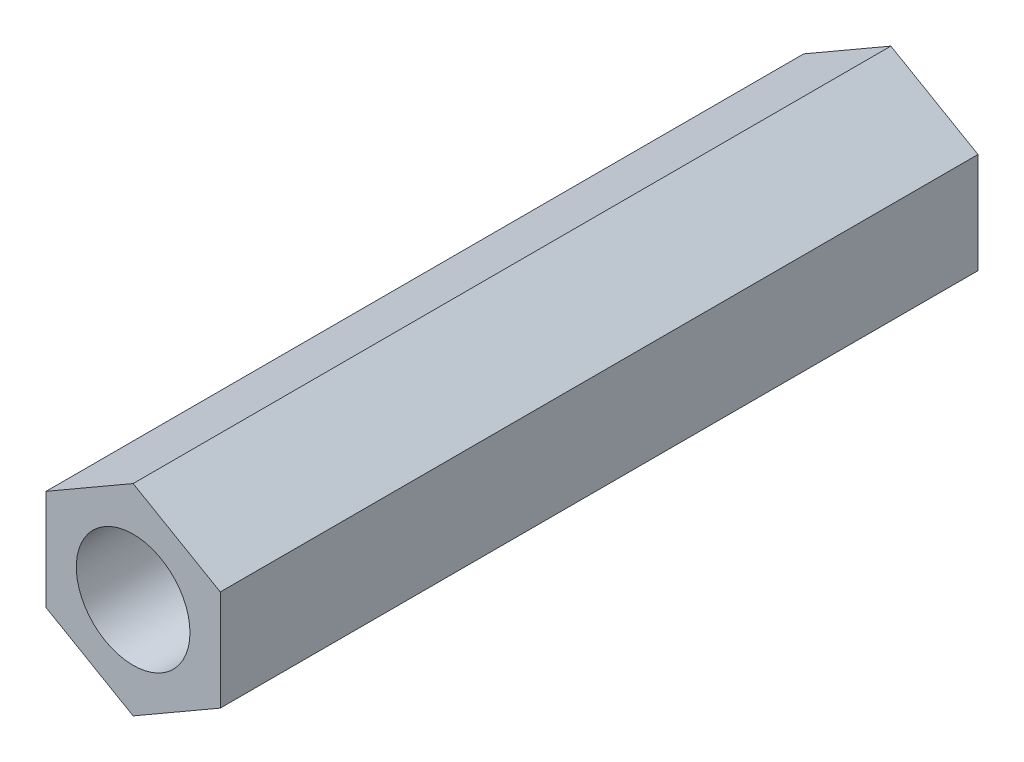
SolidWorks part; units mm, degrees
ref_plane "前视基准面" through (0, 0, 0) normal (0, 0, 1) x (1, 0, 0)
ref_plane "上视基准面" through (0, 0, 0) normal (0, 1, 0) x (1, 0, 0)
ref_plane "右视基准面" through (0, 0, 0) normal (1, 0, 0) x (0, 0, -1)
sketch "草图1" plane through (0, 0, 0) normal (0, 0, 1) x (1, 0, 0)
  line L1 (2.3, 1.3279) -> (0, 2.6558)
  line L2 (0, 2.6558) -> (-2.3, 1.3279)
  line L3 (-2.3, 1.3279) -> (-2.3, -1.3279)
  line L4 (-2.3, -1.3279) -> (0, -2.6558)
  line L5 (0, -2.6558) -> (2.3, -1.3279)
  line L6 (2.3, -1.3279) -> (2.3, 1.3279)
  circle A0 centre (0, 0) radius 2.3 construction
  circle A1 centre (0, 0) radius 1.5
  dimension "D1" = 3
  dimension "D2" = 4.6
extrude "凸台-拉伸1" add sketch "草图1" along normal blind 20
